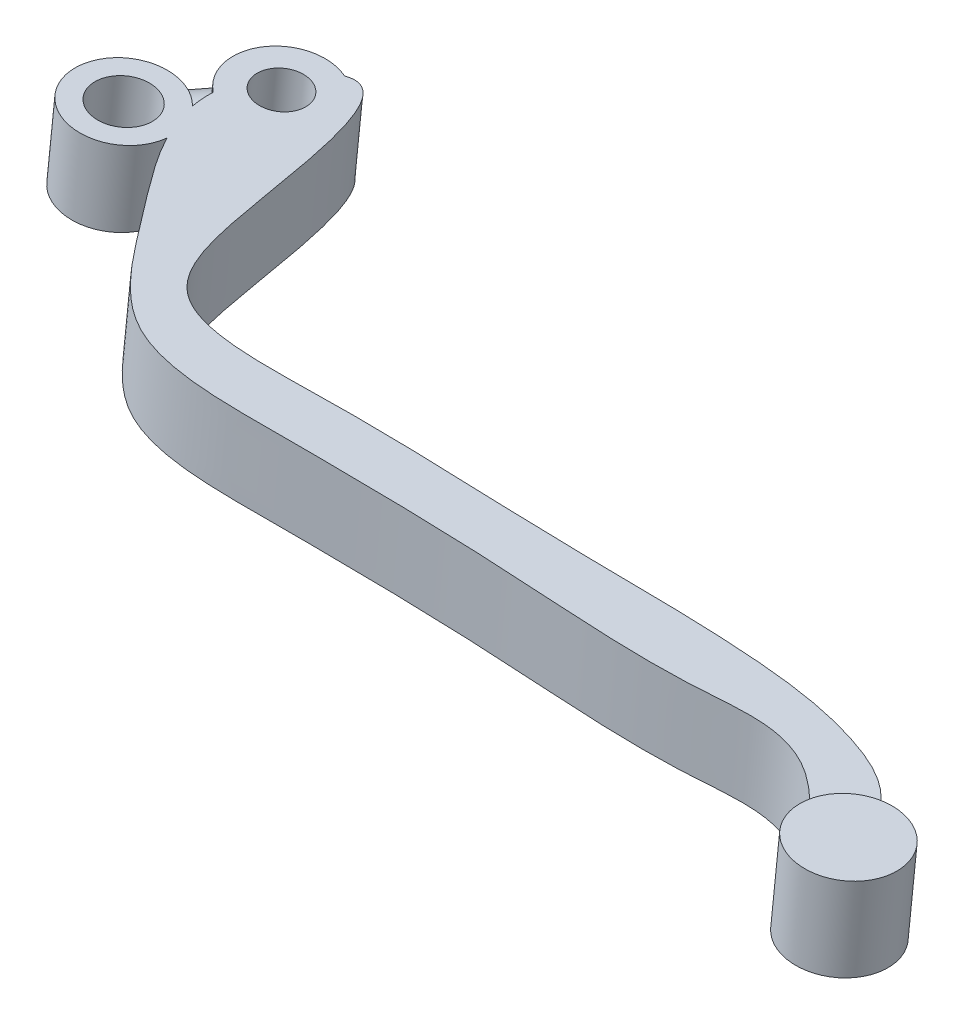
SolidWorks part; units mm, degrees
material "Aleación 6061"
ref_plane "Alzado" through (0, 0, 0) normal (0, 0, 1) x (1, 0, 0)
ref_plane "Planta" through (0, 0, 0) normal (0, 1, 0) x (1, 0, 0)
ref_plane "Vista lateral" through (0, 0, 0) normal (1, 0, 0) x (0, 0, -1)
sketch3d "Sk_puntos_Plano_palanca"
  point P0 (247.8038, 40.2316, -26.1614)
  point P1 (297.3062, 35.1814, -31.0616)
  point P2 (252.6788, 39.7343, 23.5979)
ref_plane "Plano_palanca" through (6.6148, 64.8378, 0) normal (-0.1015, -0.9948, 0) x (-0.9948, 0.1015, 0)
sketch "Sk_Palanca" plane through (6.6148, 64.8378, 0) normal (-0.1015, -0.9948, 0) x (-0.9948, 0.1015, 0)
  spline S0 degree 3 poles (-254.9118, 3.3768) (-241.8709, -13.9666) (-252.1672, -26.5391) (-262.1509, -40.9172) (-282.5977, -38.6131) (-302.0678, -36.9124) (-321.774, -36.7308) (-335.8922, -32.7728) (-346.4274, -47.4224) (-345.1262, -34.2001) (-335.6003, -29.8606) (-321.0748, -29.329) (-301.3541, -31.6126) (-282.7257, -32.1429) (-261.0715, -35.6467) (-257.2358, -19.9312) (-254.9118, 3.3768) (-241.8709, -13.9666) (-252.1672, -26.5391) knots -0.158059 -0.111967 -0.033021 0 0.078946 0.135623 0.200779 0.301384 0.381877 0.43514 0.476712 0.500852 0.542424 0.595686 0.67618 0.776785 0.841941 0.888033 0.966979 1 1.078946 1.135623 1.200779 only from (-246.2677, -9.6359) to (-246.2677, -9.6359)
extrude "Palanca" add sketch "Sk_Palanca" along normal mid plane 9
sketch3d "Sk_Buje_pivote"
  line L0 (253.8287, 35.0936, 8.3663) -> (254.7422, 44.0471, 8.3663)
  dimension "D1" = 9
sweep "Buje_pivote" add path "Sk_Buje_pivote" circular profile diameter 11 parameters "D3"=11
sketch3d "Sk_Bola"
  line L0 (349.3548, 24.8454, 40.1035) -> (350.3697, 34.7938, 40.1035)
  dimension "D1" = 10
sweep "Bola" add path "Sk_Bola" circular profile diameter 11 parameters "D3"=11
sketch3d "Sk_Brazo_cabezal"
  line L0 (254.2854, 39.5704, 8.3663) -> (247.241, 40.289, 19.112)
  dimension "D1" = 12.869
sweep "Brazo_cabezal" add path "Sk_Brazo_cabezal" circular profile diameter 8 parameters "D3"=8
sketch3d "Sk_Oreja_cabezal"
  line L0 (246.7843, 35.8123, 19.112) -> (247.6978, 44.7658, 19.112)
  dimension "D1" = 9
sweep "Oreja_cabezal" add path "Sk_Oreja_cabezal" circular profile diameter 11 parameters "D3"=11
sketch3d "Sk_Agujero_pivote"
  line L0 (253.4735, 31.6117, 8.3663) -> (255.0974, 47.5291, 8.3663)
  dimension "D1" = 16
sweep "Agujero_pivote" cut path "Sk_Agujero_pivote" circular profile diameter 5.5 parameters "D3"=5.5
sketch3d "Sk_Alojamiento_cabezal"
  line L0 (246.6321, 34.32, 19.112) -> (247.85, 46.2581, 19.112)
  dimension "D1" = 12
sweep "Alojamiento_cabezal" cut path "Sk_Alojamiento_cabezal" circular profile diameter 6.5 parameters "D3"=6.5
sketch3d "Sk_Salida_cable"
  line L0 (247.241, 40.289, 19.112) -> (238.5451, 41.1762, 22.1835)
  dimension "D1" = 9.265
sweep "Salida_cable" cut path "Sk_Salida_cable" circular profile diameter 2 parameters "D3"=2
